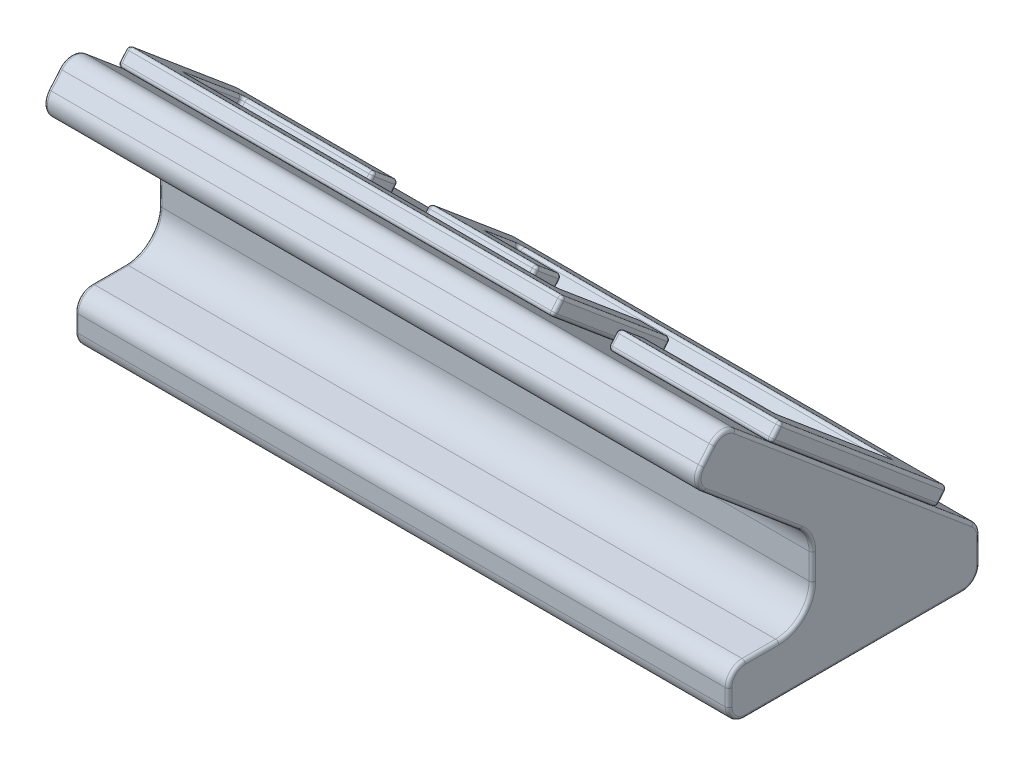
SolidWorks part; units mm, degrees
ref_plane "Front Plane" through (0, 0, 0) normal (0, 0, 1) x (1, 0, 0)
ref_plane "Top Plane" through (0, 0, 0) normal (0, 1, 0) x (1, 0, 0)
ref_plane "Right Plane" through (0, 0, 0) normal (1, 0, 0) x (0, 0, -1)
sketch "Sketch2" plane through (0, 0, 0) normal (1, 0, 0) x (0, 0, -1)
  line L0 (0, 0) -> (15, 0)
  line L1 (15, 0) -> (15, 3)
  line L2 (15, 3) -> (-0.3209, 15.8558)
  line L3 (-0.3209, 15.8558) -> (-2.2493, 13.5576)
  line L4 (-2.2493, 13.5576) -> (5, 7.4748)
  line L5 (5, 7.4748) -> (5, 3)
  line L6 (5, 3) -> (0, 3)
  line L7 (0, 3) -> (0, 0)
  dimension "D1" = 15
  dimension "D2" = 3
  dimension "D3" = 20
  dimension "D4" = 3
  dimension "D5" = 3
  dimension "D6" = 5
  dimension "D7" = 40
extrude "Boss-Extrude1" add sketch "Sketch2" along normal blind 39
fillet "Fillet1" radius 1 6 edges at (19.5, 3, 0) (19.5, 0, 0) (19.5, 13.5576, 2.2493) (19.5, 15.8558, 0.3209) (19.5, 0, -15) (19.5, 3, -15)
fillet "Fillet2" radius 2 2 edges at (19.5, 7.4748, -5) (19.5, 3, -5)
sketch "Sketch3" plane through (0, 9.1465, -7.6749) normal (0, 0.766, -0.6428) x (1, 0, 0)
  line L0 (25.9832, -6.7398) -> (25.9832, 1.7102)
  line L1 (25.9832, 1.7102) -> (24.0332, 1.7102)
  line L2 (24.0332, 1.7102) -> (24.0332, -4.7898)
  line L3 (24.0332, -4.7898) -> (1.9332, -4.7898)
  line L4 (1.9332, -4.7898) -> (1.9332, -0.2398)
  line L5 (1.9332, -0.2398) -> (9.7332, -0.2398)
  line L6 (9.7332, -0.2398) -> (9.7332, 1.7102)
  line L7 (9.7332, 1.7102) -> (-0.0168, 1.7102)
  line L8 (-0.0168, 1.7102) -> (-0.0168, -6.7398)
  line L9 (-0.0168, -6.7398) -> (25.9832, -6.7398)
  line L10 (38.9832, -6.7398) -> (38.9832, 6.2602)
  line L11 (38.9832, 6.2602) -> (12.9832, 6.2602)
  line L12 (12.9832, 6.2602) -> (12.9832, -0.2398)
  line L13 (12.9832, -0.2398) -> (19.4832, -0.2398)
  line L14 (19.4832, -0.2398) -> (19.4832, 1.7102)
  line L15 (19.4832, 1.7102) -> (14.9332, 1.7102)
  line L16 (14.9332, 1.7102) -> (14.9332, 4.3102)
  line L17 (14.9332, 4.3102) -> (37.0332, 4.3102)
  line L18 (37.0332, 4.3102) -> (37.0332, -4.7898)
  line L19 (37.0332, -4.7898) -> (29.2332, -4.7898)
  line L20 (29.2332, -4.7898) -> (29.2332, -6.7398)
  line L21 (29.2332, -6.7398) -> (38.9832, -6.7398)
extrude "Boss-Extrude2" add sketch "Sketch3" along normal blind 1 separate body
fillet "Fillet3" radius 0.2 32 edges at (0, 0.2929, -0.2929) (0, 0, -7.5) (0, 0.2929, -14.7071) (0, 1.7668, -15) (0, 2.9563, -14.9063) (0, 9.2564, -7.544) (0, 15.4431, 0.2848) (0, 14.7067, 1.2851) (0, 13.5937, 1.8366) (0, 10.4945, -1.4012) (0, 7.3874, -4.8126) (0, 5.7711, -5) (0, 3.5858, -4.4142) (0, 3, -2) (0, 2.7071, -0.2929) (0, 1.5, 0) (39, 7.3874, -4.8126) (39, 10.4945, -1.4012) (39, 13.5937, 1.8366) (39, 14.7067, 1.2851) (39, 15.4431, 0.2848) (39, 9.2564, -7.544) (39, 2.9563, -14.9063) (39, 1.7668, -15) (39, 0.2929, -14.7071) (39, 0, -7.5) (39, 0.2929, -0.2929) (39, 1.5, 0) (39, 2.7071, -0.2929) (39, 3, -2) (39, 3.5858, -4.4142) (39, 5.7711, -5)
fillet "Fillet4" radius 0.2 36 edges at (34.1082, 14.2448, -3.1547) (34.1082, 13.4788, -2.5119) (29.2332, 13.6181, -3.9016) (29.2332, 13.8618, -2.8333) (29.2332, 12.8521, -3.2588) (33.1332, 12.9914, -4.6485) (29.2332, 12.6084, -4.3271) (33.1332, 12.2253, -4.0057) (37.0332, 10.0667, -8.134) (37.0332, 12.6084, -4.3271) (37.0332, 9.3007, -7.4912) (25.9832, 7.142, -11.6195) (37.0332, 6.759, -11.2981) (25.9832, 6.376, -10.9767) (17.2082, 8.8133, -9.6278) (17.2082, 8.0472, -8.985) (16.2332, 10.0667, -8.134) (16.2332, 9.3007, -7.4912) (19.4832, 9.6837, -7.8126) (19.4832, 9.44, -8.8809) (19.4832, 8.4302, -9.3064) (19.4832, 8.6739, -8.2381) (14.9332, 8.4302, -9.3064) (14.9332, 7.9776, -10.6236) (14.9332, 6.759, -11.2981) (14.9332, 7.2116, -9.9808) (12.9832, 7.9776, -10.6236) (12.9832, 9.6837, -7.8126) (12.9832, 7.2116, -9.9808) (25.9832, 5.8886, -13.1133) (12.9832, 5.5056, -12.7919) (25.9832, 5.1225, -12.4705) (38.9832, 13.8618, -2.8333) (38.9832, 10.0667, -8.134) (38.9832, 5.5056, -12.7919) (38.9832, 9.3007, -7.4912)
fillet "Fillet5" radius 0.2 30 edges at (-0.0168, 10.763, -5.7484) (-0.0168, 13.8618, -2.8333) (12.9832, 13.4788, -2.5119) (5.8332, 9.3007, -7.4912) (1.9332, 9.6837, -7.8126) (1.9332, 10.763, -5.7484) (-0.0168, 8.4302, -9.3064) (4.8582, 8.0472, -8.985) (9.7332, 9.6837, -7.8126) (9.7332, 8.4302, -9.3064) (9.7332, 8.6739, -8.2381) (25.0082, 8.0472, -8.985) (24.0332, 8.4302, -9.3064) (24.0332, 10.1363, -6.4953) (24.0332, 12.6084, -4.3271) (1.9332, 12.6084, -4.3271) (12.9832, 12.2253, -4.0057) (25.9832, 13.8618, -2.8333) (25.9832, 8.4302, -9.3064) (25.9832, 10.763, -5.7484) (-0.0168, 11.529, -6.3912) (4.8582, 8.8133, -9.6278) (9.7332, 9.44, -8.8809) (5.8332, 10.0667, -8.134) (1.9332, 11.529, -6.3912) (12.9832, 12.9914, -4.6485) (24.0332, 10.9023, -7.1381) (25.0082, 8.8133, -9.6278) (25.9832, 11.529, -6.3912) (12.9832, 14.2448, -3.1547)
